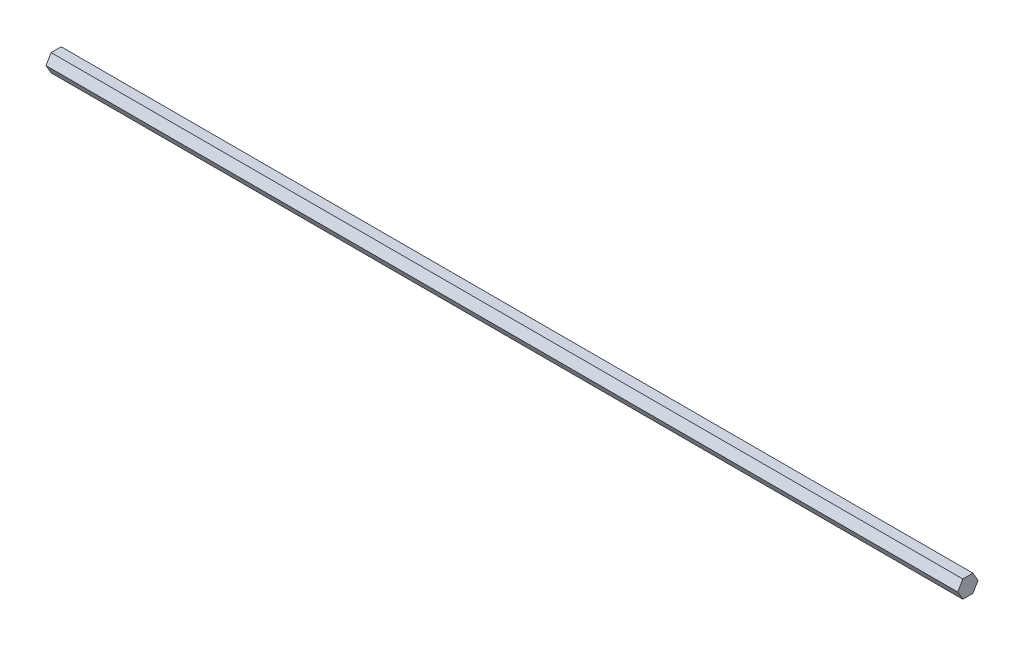
SolidWorks part; units mm, degrees
ref_plane "Alzado" through (0, 0, 0) normal (0, 0, 1) x (1, 0, 0)
ref_plane "Planta" through (0, 0, 0) normal (0, 1, 0) x (1, 0, 0)
ref_plane "Vista lateral" through (0, 0, 0) normal (1, 0, 0) x (0, 0, -1)
sketch "Croquis1" plane through (0, 0, 0) normal (1, 0, 0) x (0, 0, -1)
  line L1 (7.3323, 0) -> (3.6662, 6.35)
  line L2 (3.6662, 6.35) -> (-3.6662, 6.35)
  line L3 (-3.6662, 6.35) -> (-7.3323, 0)
  line L4 (-7.3323, 0) -> (-3.6662, -6.35)
  line L5 (-3.6662, -6.35) -> (3.6662, -6.35)
  line L6 (3.6662, -6.35) -> (7.3323, 0)
  circle A0 centre (0, 0) radius 6.35 construction
  dimension "D1" = 12.7
extrude "Saliente-Extruir1" add sketch "Croquis1" along normal blind 660
